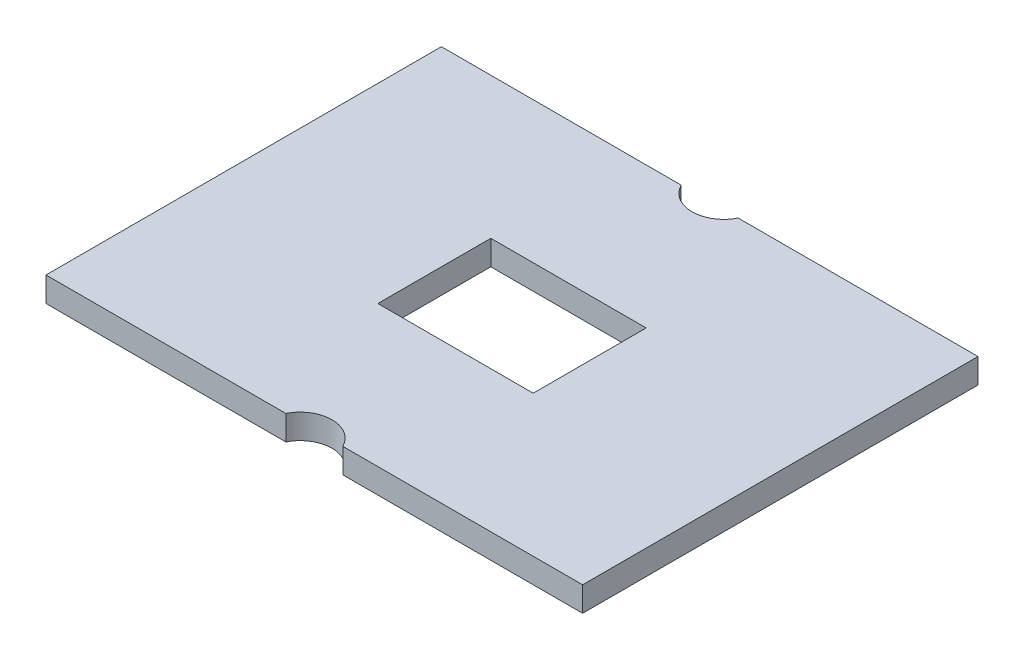
SolidWorks part; units mm, degrees
ref_plane "Front Plane" through (0, 0, 0) normal (0, 0, 1) x (1, 0, 0)
ref_plane "Top Plane" through (0, 0, 0) normal (0, 1, 0) x (1, 0, 0)
ref_plane "Right Plane" through (0, 0, 0) normal (1, 0, 0) x (0, 0, -1)
sketch "Sketch1" plane through (0, 0, 0) normal (0, 1, 0) x (1, 0, 0)
  line L1 (-38, -28) -> (38, -28)
  line L2 (-38, -28) -> (-38, 28)
  line L3 (-38, 28) -> (38, 28)
  line L4 (38, -28) -> (38, 28)
  line L5 (-38, -28) -> (38, 28) construction
  line L6 (-38, 28) -> (38, -28) construction
  point P0 (0, 0)
extrude "Boss-Extrude1" add sketch "Sketch1" along normal blind 3.5
sketch "Sketch2" plane through (0, 0, 0) normal (0, -1, 0) x (1, 0, 0)
  line L1 (-11, -8) -> (11, -8)
  line L2 (-11, -8) -> (-11, 8)
  line L3 (-11, 8) -> (11, 8)
  line L4 (11, -8) -> (11, 8)
  line L5 (-11, -8) -> (11, 8) construction
  line L6 (-11, 8) -> (11, -8) construction
  circle A0 centre (0, -30) radius 4.5
  circle A1 centre (0, 30) radius 4.5
  point P4 (0, 0)
extrude "Cut-Extrude1" cut sketch "Sketch2" against normal blind 3.5
